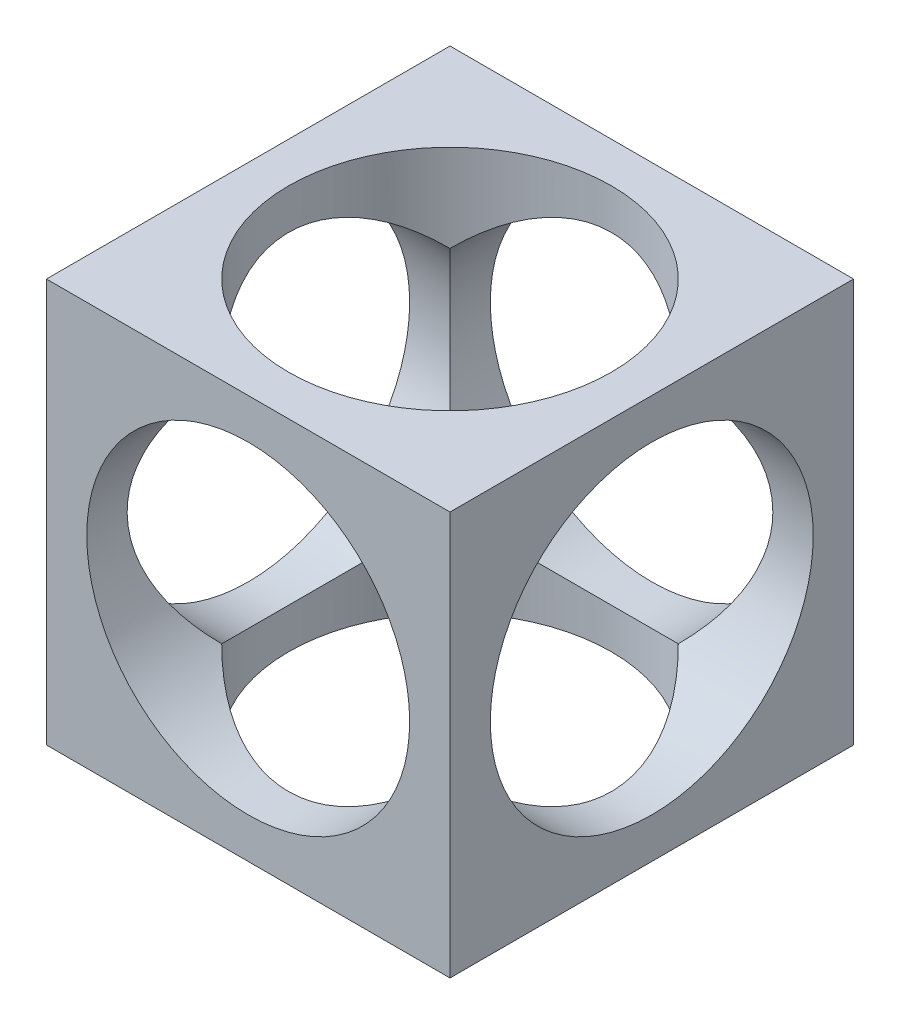
SolidWorks part; units mm, degrees
ref_plane "Alzado" through (0, 0, 0) normal (0, 0, 1) x (1, 0, 0)
ref_plane "Planta" through (0, 0, 0) normal (0, 1, 0) x (1, 0, 0)
ref_plane "Vista lateral" through (0, 0, 0) normal (1, 0, 0) x (0, 0, -1)
sketch "Croquis1" plane through (0, 0, 0) normal (0, 0, 1) x (1, 0, 0)
  line L1 (0, 0) -> (100, 0)
  line L2 (0, 0) -> (0, 100)
  line L3 (0, 100) -> (100, 100)
  line L4 (100, 0) -> (100, 100)
  dimension "D1" = 100
  dimension "D2" = 100
extrude "Saliente-Extruir1" add sketch "Croquis1" along normal blind 100 contours L1 L4 L3 L2
sketch "Croquis2" plane through (0, 0, 100) normal (0, 0, 1) x (1, 0, 0)
  line L0 (0, 0) -> (0, 100) construction
  line L2 (0, 100) -> (100, 100) construction
  circle A0 centre (50, 50) radius 40
  dimension "D1" = 50
  dimension "D2" = 50
extrude "Cortar-Extruir1" cut sketch "Croquis2" against normal blind 100
sketch "Croquis3" plane through (100, 0, 0) normal (1, 0, 0) x (0, 0, -1)
  line L0 (-100, 0) -> (-100, 100) construction
  line L2 (-100, 100) -> (0, 100) construction
  circle A0 centre (-50, 50) radius 40
  dimension "D1" = 50
  dimension "D2" = 50
extrude "Cortar-Extruir2" cut sketch "Croquis3" against normal blind 100 contours A0
sketch "Croquis4" plane through (0, 100, 0) normal (0, 1, 0) x (1, 0, 0)
  line L0 (0, -100) -> (0, 0) construction
  line L1 (0, 0) -> (100, 0) construction
  circle A0 centre (50, -50) radius 40
  dimension "D1" = 50
  dimension "D2" = 50
extrude "Cortar-Extruir3" cut sketch "Croquis4" against normal blind 100
